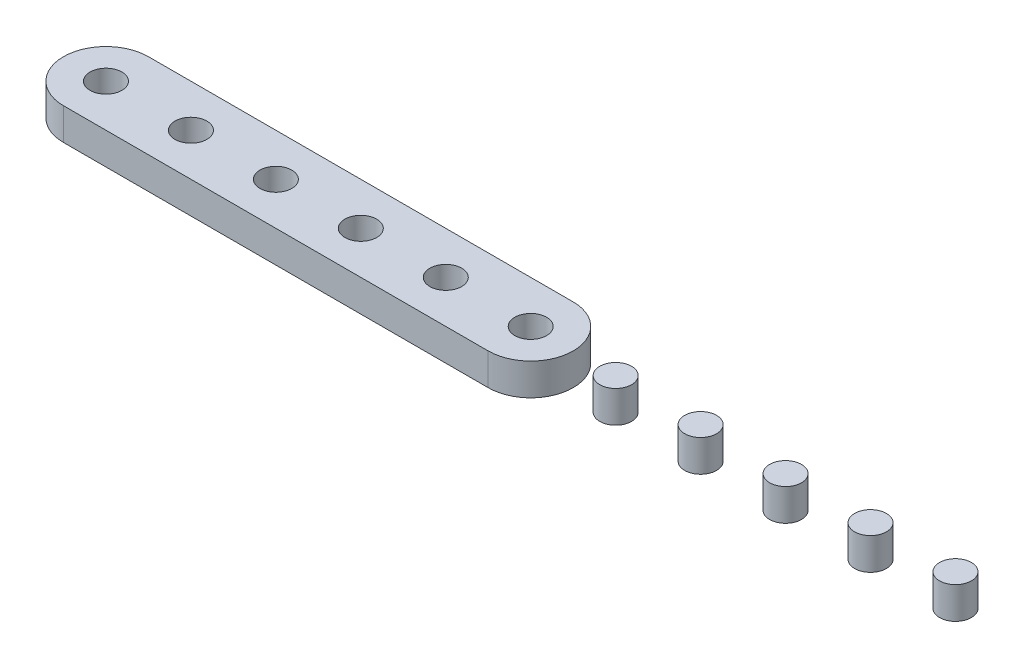
SolidWorks part; units mm, degrees
ref_plane "Front Plane" through (0, 0, 0) normal (0, 0, 1) x (1, 0, 0)
ref_plane "Top Plane" through (0, 0, 0) normal (0, 1, 0) x (1, 0, 0)
ref_plane "Right Plane" through (0, 0, 0) normal (1, 0, 0) x (0, 0, -1)
sketch "Sketch2" plane through (0, 0, 0) normal (0, 1, 0) x (1, 0, 0)
  line L0 (0, 0) -> (40, 0) construction
  line L1 (0, 4) -> (40, 4)
  line L2 (0, -4) -> (40, -4)
  arc A0 (0, 4) -> (0, -4) centre (0, 0) ccw
  arc A1 (40, -4) -> (40, 4) centre (40, 0) ccw
  circle A2 centre (0, 0) radius 1.5
  circle A3 centre (8, 0) radius 1.5
  circle A4 centre (16, 0) radius 1.5
  circle A5 centre (24, 0) radius 1.5
  circle A6 centre (32, 0) radius 1.5
  circle A7 centre (40, 0) radius 1.5
  circle A8 centre (48, 0) radius 1.5
  circle A9 centre (56, 0) radius 1.5
  circle A10 centre (64, 0) radius 1.5
  circle A11 centre (72, 0) radius 1.5
  circle A12 centre (80, 0) radius 1.5
  point P3 (20, 0)
  dimension "D1" = 3
  dimension "D2" = 8
  dimension "D3" = 40
extrude "Boss-Extrude2" add sketch "Sketch2" along normal blind 3
